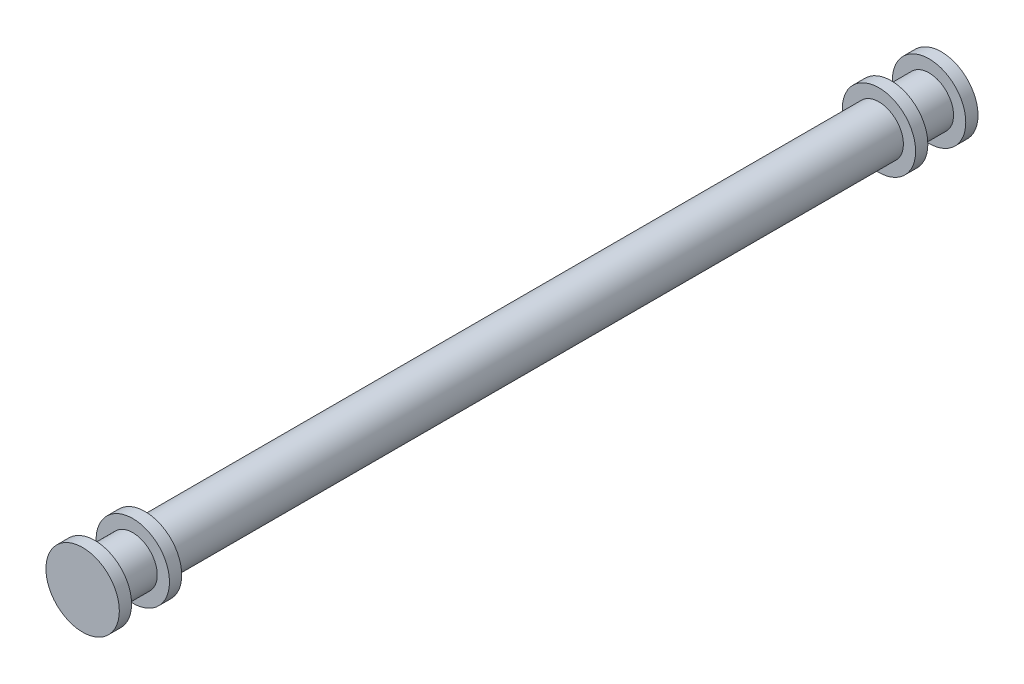
SolidWorks part; units mm, degrees
ref_plane "Спереди" through (0, 0, 0) normal (0, 0, 1) x (1, 0, 0)
ref_plane "Сверху" through (0, 0, 0) normal (0, 1, 0) x (1, 0, 0)
ref_plane "Справа" through (0, 0, 0) normal (1, 0, 0) x (0, 0, -1)
sketch "Эскиз1" plane through (0, 0, 0) normal (0, 0, 1) x (1, 0, 0)
  circle A0 centre (0, 0) radius 4
  dimension "D1" = 8
extrude "Бобышка-Вытянуть1" add sketch "Эскиз1" along normal mid plane 120
sketch "Эскиз2" plane through (0, 0, 60) normal (0, 0, 1) x (1, 0, 0)
  circle A0 centre (0, 0) radius 6
  dimension "D1" = 12
extrude "Бобышка-Вытянуть2" add sketch "Эскиз2" along normal blind 2
sketch "Эскиз3" plane through (0, 0, 62) normal (0, 0, 1) x (1, 0, 0)
  circle A0 centre (0, 0) radius 4 construction
  circle A1 centre (0, 0) radius 4
extrude "Бобышка-Вытянуть3" add sketch "Эскиз3" along normal blind 6.2
sketch "Эскиз4" plane through (0, 0, 68.2) normal (0, 0, 1) x (1, 0, 0)
  circle A0 centre (0, 0) radius 6 construction
  circle A1 centre (0, 0) radius 6
extrude "Бобышка-Вытянуть4" add sketch "Эскиз4" along normal blind 2
mirror "Зеркальное отражение1" about plane through (0, 0, 0) normal (0, 0, 1) of "Бобышка-Вытянуть2", "Бобышка-Вытянуть3", "Бобышка-Вытянуть4"
